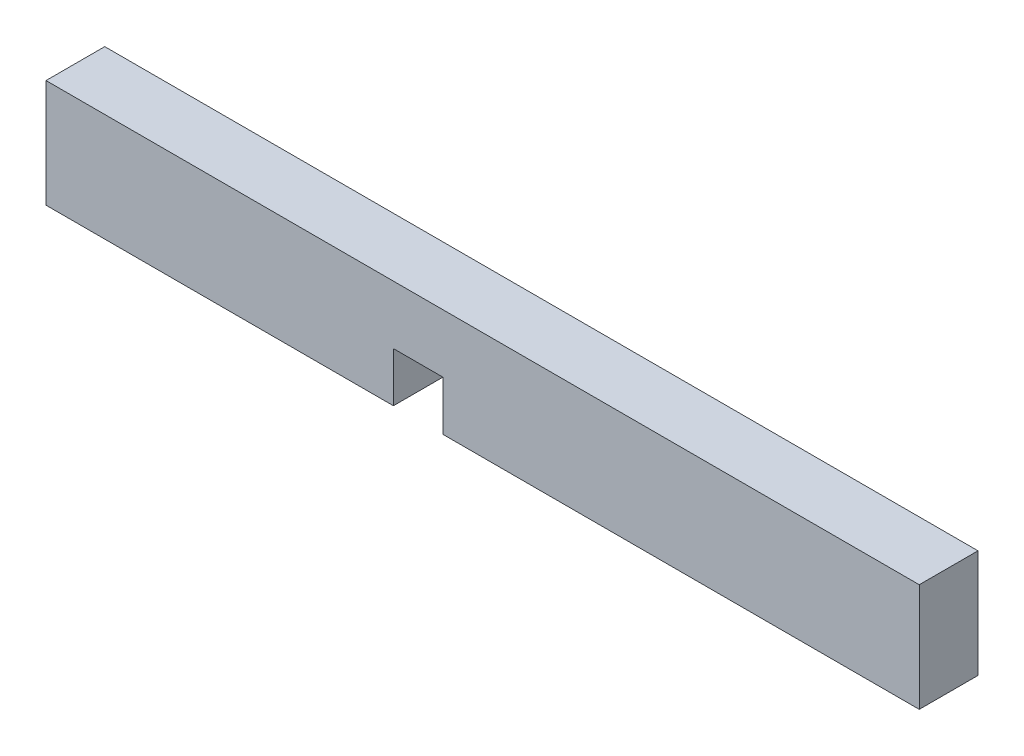
SolidWorks part; units mm, degrees
ref_plane "Front" through (0, 0, 0) normal (0, 0, 1) x (1, 0, 0)
ref_plane "Top" through (0, 0, 0) normal (0, 1, 0) x (1, 0, 0)
ref_plane "Right" through (0, 0, 0) normal (1, 0, 0) x (0, 0, -1)
sketch "Sketch1" plane through (0, 0, 0) normal (0, 0, 1) x (1, 0, 0)
  line L0 (-3.9624, -3.9624) -> (-31.75, -3.9624)
  line L1 (38.1, 4.6736) -> (-31.75, 4.6736)
  line L2 (38.1, 4.6736) -> (38.1, -3.9624)
  line L3 (38.1, -3.9624) -> (0, -3.9624)
  line L4 (-31.75, 4.6736) -> (-31.75, -3.9624)
  line L5 (-3.9624, -3.9624) -> (0, -3.9624) construction
  line L6 (0, -3.9624) -> (0, 0)
  line L8 (-3.9624, -3.9624) -> (-3.9624, 0)
  line L11 (-3.9624, 0) -> (0, 0)
  point P0 (0, 0)
  point P7 (0, 0)
  point P8 (-3.9624, -1.9812)
  dimension "D1" = 69.85
  dimension "D2" = 8.636
  dimension "D3" = 27.7876
  dimension "D4" = 3.9624
  dimension "D5" = 3.9624
extrude "Boss-Extrude1" add sketch "Sketch1" along normal blind 4.699
